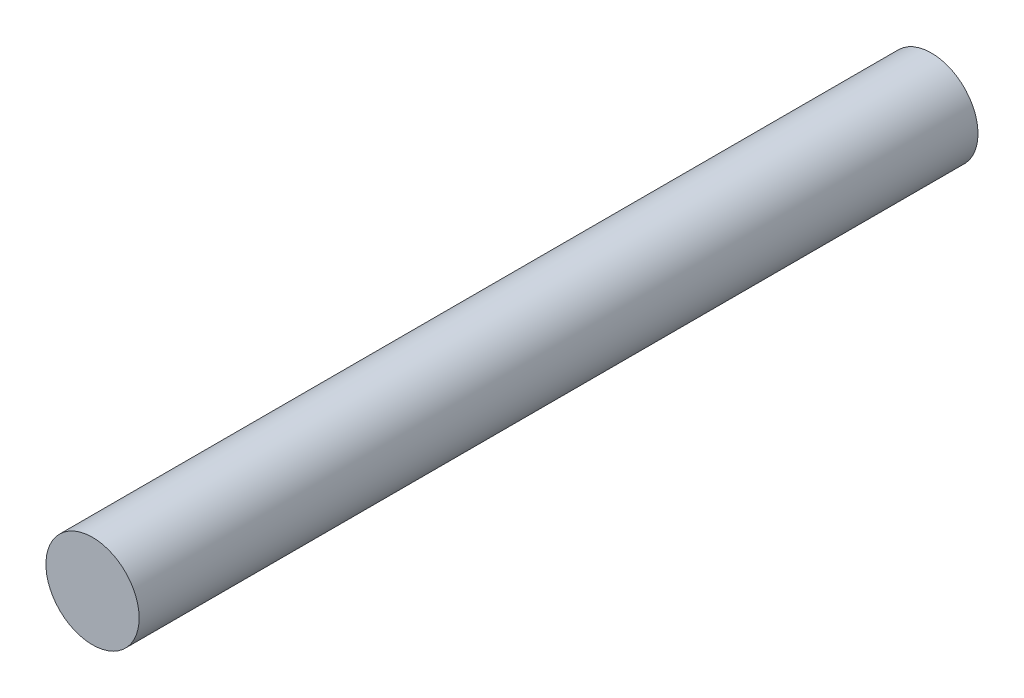
SolidWorks part; units mm, degrees
ref_plane "Alzado" through (0, 0, 0) normal (0, 0, 1) x (1, 0, 0)
ref_plane "Planta" through (0, 0, 0) normal (0, 1, 0) x (1, 0, 0)
ref_plane "Vista lateral" through (0, 0, 0) normal (1, 0, 0) x (0, 0, -1)
sketch "Croquis1" plane through (0, 0, 0) normal (0, 0, 1) x (1, 0, 0)
  circle A0 centre (0, 0) radius 2.95
extrude "Saliente-Extruir1" add sketch "Croquis1" along normal blind 53.1
